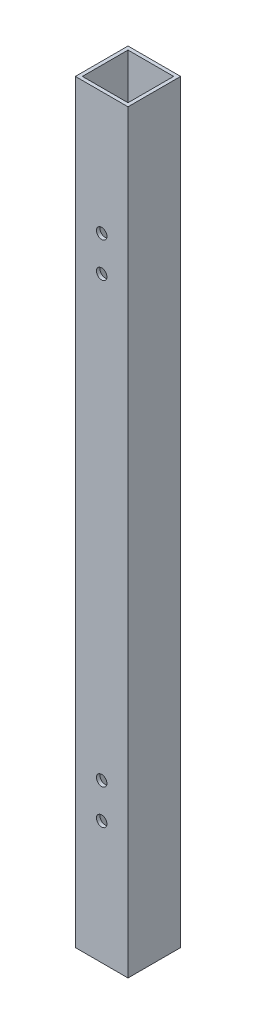
SolidWorks part; units mm, degrees
ref_plane "Front Plane" through (0, 0, 0) normal (0, 0, 1) x (1, 0, 0)
ref_plane "Top Plane" through (0, 0, 0) normal (0, 1, 0) x (1, 0, 0)
ref_plane "Right Plane" through (0, 0, 0) normal (1, 0, 0) x (0, 0, -1)
sketch "Sketch1" plane through (0, 0, 0) normal (0, 1, 0) x (1, 0, 0)
  line L1 (-15, 0) -> (-15, 15)
  line L2 (-15, 15) -> (15, 15)
  line L3 (15, 15) -> (15, -15)
  line L4 (15, -15) -> (-15, -15)
  line L5 (-15, -15) -> (-15, 0)
extrude "Boss-Extrude1" add sketch "Sketch1" along normal blind 430
sketch "Sketch2" plane through (0, 430, 0) normal (0, 1, 0) x (1, 0, 0)
  line L3 (-13, 13) -> (-13, -13)
  line L4 (-13, -13) -> (13, -13)
  line L5 (13, -13) -> (13, 13)
  line L6 (13, 13) -> (-13, 13)
extrude "Cut-Extrude1" cut sketch "Sketch2" against normal blind 430
sketch "Sketch3" plane through (0, 0, 15) normal (0, 0, 1) x (1, 0, 0)
  circle A0 centre (0, 360) radius 3
  circle A1 centre (0, 340) radius 3
  circle A2 centre (0, 90) radius 3
  circle A3 centre (0, 70) radius 3
extrude "Cut-Extrude2" cut sketch "Sketch3" against normal blind 30
